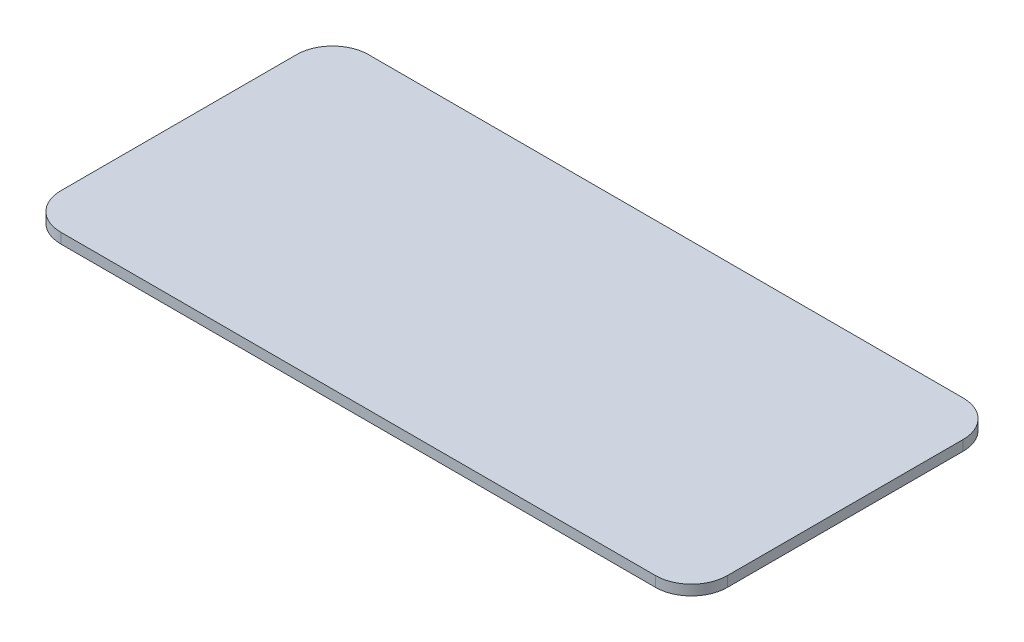
SolidWorks part; units mm, degrees
ref_plane "Front Plane" through (0, 0, 0) normal (0, 0, 1) x (1, 0, 0)
ref_plane "Top Plane" through (0, 0, 0) normal (0, 1, 0) x (1, 0, 0)
ref_plane "Right Plane" through (0, 0, 0) normal (1, 0, 0) x (0, 0, -1)
sketch "Sketch1" plane through (0, 0, 0) normal (0, 1, 0) x (1, 0, 0)
  line L1 (-25.5236, 29.4956) -> (32.4764, 29.4956)
  line L2 (-29.0236, 25.9956) -> (-29.0236, 2.9956)
  line L3 (-25.5236, -0.5044) -> (32.4764, -0.5044)
  line L4 (35.9764, 25.9956) -> (35.9764, 2.9956)
  line L5 (-25.5236, 25.9956) -> (32.4764, 25.9956)
  line L6 (-25.5236, 25.9956) -> (-25.5236, 2.9956)
  line L7 (-25.5236, 2.9956) -> (32.4764, 2.9956)
  line L8 (32.4764, 25.9956) -> (32.4764, 2.9956)
  line L16 (-33.0936, 16.3956) -> (-30.505, 16.3956)
  line L17 (12.3764, -1.404) -> (12.3764, -2.6868)
  line L18 (24.9764, -1.404) -> (24.9764, -2.6868)
  arc A0 (-25.5236, 29.4956) -> (-29.0236, 25.9956) centre (-25.5236, 25.9956) ccw
  arc A5 (-25.5236, -0.5044) -> (-29.0236, 2.9956) centre (-25.5236, 2.9956) cw
  arc A6 (32.4764, -0.5044) -> (35.9764, 2.9956) centre (32.4764, 2.9956) ccw
  arc A7 (35.9764, 25.9956) -> (32.4764, 29.4956) centre (32.4764, 25.9956) ccw
  dimension "D15" = 3.5
  dimension "D1" = 30
  dimension "D2" = 23
  dimension "D4" = 3.5
  dimension "D12" = 16.9
  dimension "D13" = 41.4
  dimension "D14" = 54
extrude "Boss-Extrude1" add sketch "Sketch1" along normal blind 1 contours L3 A6 L4 A7 L1 A0 L2 A5
